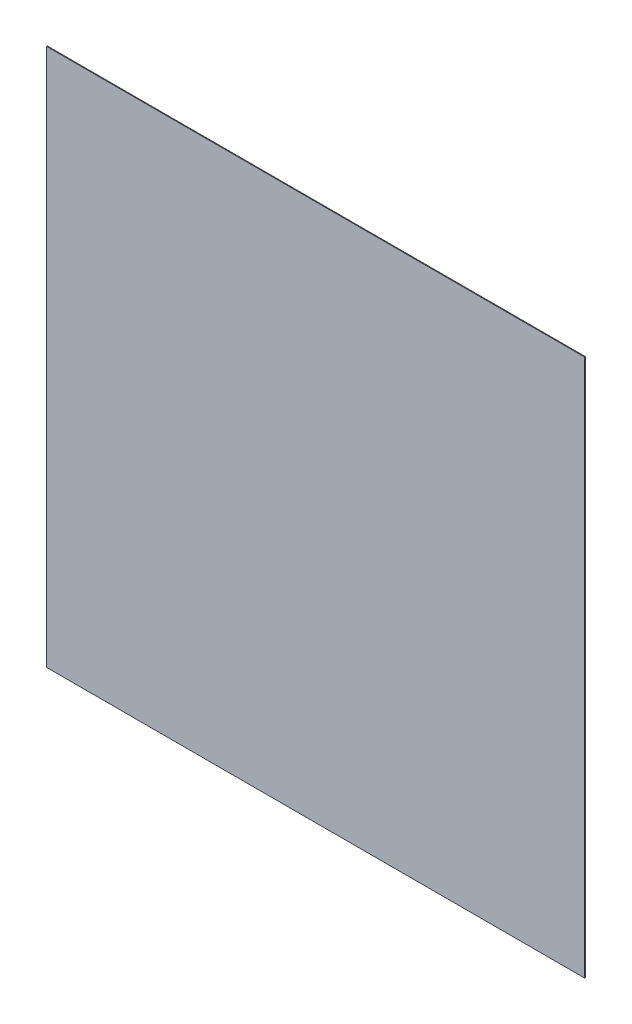
SolidWorks part; units mm, degrees
ref_plane "正面" through (0, 0, 0) normal (0, 0, 1) x (1, 0, 0)
ref_plane "平面" through (0, 0, 0) normal (0, 1, 0) x (1, 0, 0)
ref_plane "右側面" through (0, 0, 0) normal (1, 0, 0) x (0, 0, -1)
sketch "ｽｹｯﾁ2" plane through (0, 0, 0) normal (0, 0, 1) x (1, 0, 0)
  line L1 (0, 0) -> (700, 0)
  line L2 (0, 0) -> (0, 700)
  line L3 (0, 700) -> (700, 700)
  line L4 (700, 0) -> (700, 700)
extrude "ﾎﾞｽ - 押し出し1" add sketch "ｽｹｯﾁ2" along normal blind 1
